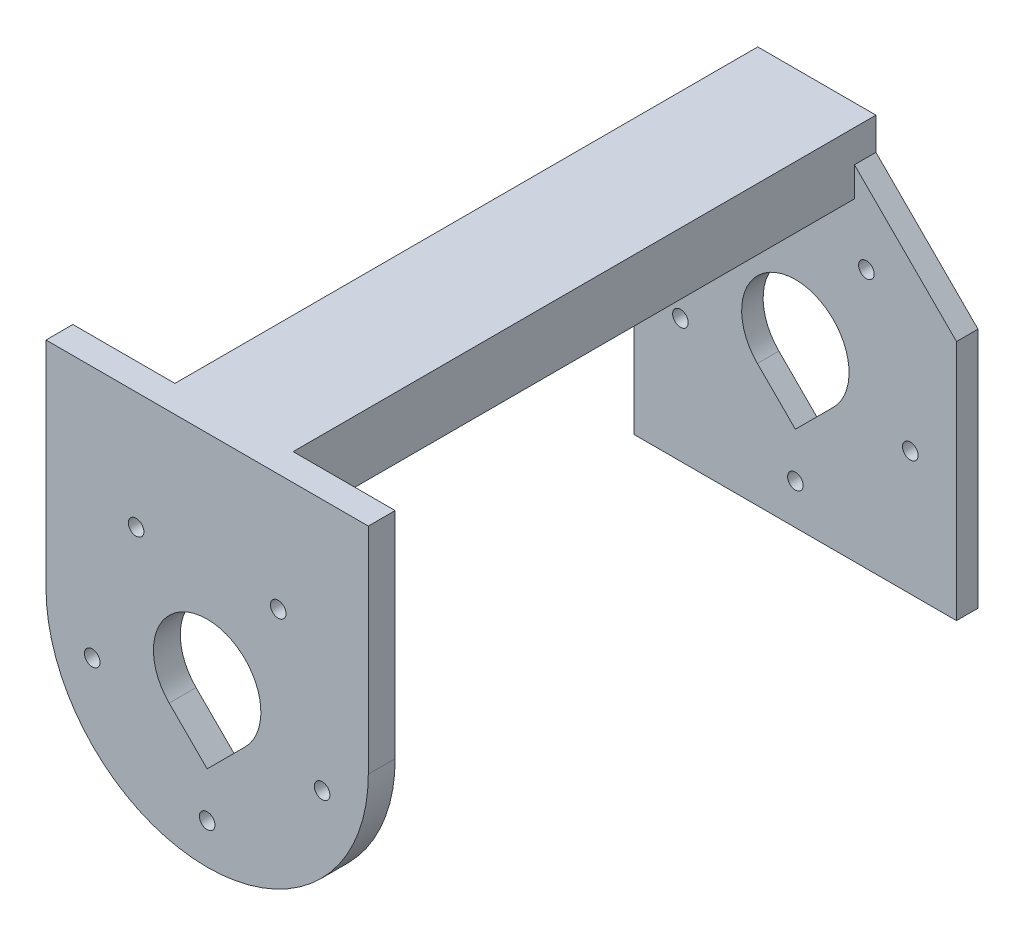
SolidWorks part; units mm, degrees
ref_plane "Front Plane" through (0, 0, 0) normal (0, 0, 1) x (1, 0, 0)
ref_plane "Top Plane" through (0, 0, 0) normal (0, 1, 0) x (1, 0, 0)
ref_plane "Right Plane" through (0, 0, 0) normal (1, 0, 0) x (0, 0, -1)
ref_plane "Plane1" through (0, 0, 384.5) normal (0, 0, 1) x (1, 0, 0)
sketch "Sketch1" plane through (0, 0, 384.5) normal (0, 0, 1) x (1, 0, 0)
  circle A0 centre (300, 300) radius 30
extrude "Boss-Extrude1" add sketch "Sketch1" along normal blind 5
sketch "Sketch2" plane through (0, 0, 384.5) normal (0, 0, 1) x (1, 0, 0)
  line L0 (270, 300) -> (330, 300)
  line L1 (330, 300) -> (330, 340)
  line L2 (330, 340) -> (270, 340)
  line L3 (270, 340) -> (270, 300)
extrude "Boss-Extrude2" add sketch "Sketch2" along normal blind 5
sketch "Sketch3" plane through (0, 0, 384.5) normal (0, 0, 1) x (1, 0, 0)
  line L0 (292.9289, 292.9289) -> (300, 285.8579)
  line L1 (300, 285.8579) -> (307.0711, 292.9289)
  arc A0 (307.0711, 292.9289) -> (292.9289, 292.9289) centre (300, 300) ccw
  circle A1 centre (286.7748, 318.2029) radius 1.45
  circle A2 centre (278.6012, 293.0471) radius 1.45
  circle A3 centre (300, 277.5) radius 1.45
  circle A4 centre (321.3988, 293.0471) radius 1.45
  circle A5 centre (313.2252, 318.2029) radius 1.45
extrude "Cut-Extrude1" cut sketch "Sketch3" along normal blind 5
ref_plane "Plane2" through (0, 0, 276) normal (0, 0, 1) x (1, 0, 0)
sketch "Sketch4" plane through (0, 0, 276) normal (0, 0, 1) x (1, 0, 0)
  line L0 (289, 340) -> (311, 340)
  line L1 (311, 340) -> (311, 334)
  line L2 (311, 334) -> (330, 315)
  line L3 (330, 315) -> (330, 270)
  line L4 (330, 270) -> (270, 270)
  line L5 (270, 270) -> (270, 315)
  line L6 (270, 315) -> (289, 334)
  line L7 (289, 334) -> (289, 340)
  line L8 (292.9289, 292.9289) -> (300, 285.8579)
  line L9 (300, 285.8579) -> (307.0711, 292.9289)
  arc A0 (307.0711, 292.9289) -> (292.9289, 292.9289) centre (300, 300) ccw
  circle A1 centre (286.7748, 318.2029) radius 1.45
  circle A2 centre (278.6012, 293.0471) radius 1.45
  circle A3 centre (300, 277.5) radius 1.45
  circle A4 centre (321.3988, 293.0471) radius 1.45
  circle A5 centre (313.2252, 318.2029) radius 1.45
extrude "Boss-Extrude3" add sketch "Sketch4" along normal blind 4
sketch "Sketch5" plane through (0, 0, 276) normal (0, 0, 1) x (1, 0, 0)
  line L0 (289, 328.5) -> (311, 328.5)
  line L1 (311, 328.5) -> (311, 340)
  line L2 (311, 340) -> (289, 340)
  line L3 (289, 340) -> (289, 328.5)
extrude "Boss-Extrude4" add sketch "Sketch5" along normal blind 108.5
